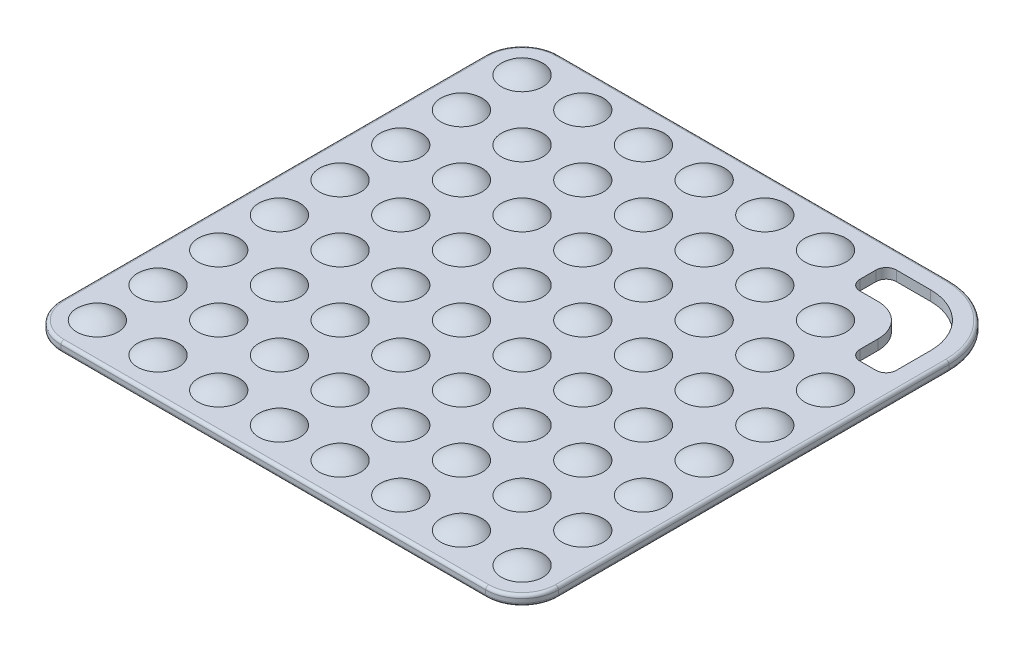
SolidWorks part; units mm, degrees
material "Natural Rubber"
ref_plane "Front Plane" through (0, 0, 0) normal (0, 0, 1) x (1, 0, 0)
ref_plane "Top Plane" through (0, 0, 0) normal (0, 1, 0) x (1, 0, 0)
ref_plane "Right Plane" through (0, 0, 0) normal (1, 0, 0) x (0, 0, -1)
sketch "Sketch1" plane through (0, 0, 0) normal (0, 1, 0) x (1, 0, 0)
  line L1 (-105, 123) -> (88, 123)
  line L2 (-123, 105) -> (-123, -105)
  line L3 (-105, -123) -> (105, -123)
  line L4 (123, 88) -> (123, -105)
  line L5 (-123, 123) -> (123, -123) construction
  line L6 (-123, -123) -> (123, 123) construction
  arc A0 (88, 123) -> (123, 88) centre (88, 88) cw
  arc A1 (105, -123) -> (123, -105) centre (105, -105) ccw
  arc A2 (-105, 123) -> (-123, 105) centre (-105, 105) ccw
  arc A3 (-123, -105) -> (-105, -123) centre (-105, -105) ccw
  point P0 (0, 0)
  dimension "D3" = 35
  dimension "D4" = 18
  dimension "D1" = 246
  dimension "D2" = 246
extrude "Boss-Extrude1" add sketch "Sketch1" along normal blind 5
ref_plane "Plane1" through (0, 0, 105) normal (0, 0, 1) x (1, 0, 0)
sketch "Sketch3" plane through (0, 0, 105) normal (0, 0, 1) x (1, 0, 0)
  line L1 (123, 5) -> (105, 5) construction
  line L2 (105, 5) -> (115.198, 5)
  line L3 (105, 9) -> (105, 5)
  arc A0 (105, 9) -> (115.198, 5) centre (105, -6) cw
  dimension "D1" = 4
  dimension "D2" = 15
revolve "Revolve4" add sketch "Sketch3" angle 360 about L3
pattern_linear "LPattern1" count 8 spacing 30 along (-1, 0, 0) count 8 spacing 30 along (0, 0, -1) skipping (0, 6), (0, 7), (1, 7) of "Revolve4"
sketch "Sketch4" plane through (0, 0, 0) normal (0, 1, 0) x (1, 0, 0)
  line L0 (88, 114) -> (71, 114)
  line L1 (66, 109) -> (66, 101)
  line L2 (71, 96) -> (80, 96)
  line L3 (96, 80) -> (96, 71)
  line L4 (101, 66) -> (109, 66)
  line L5 (114, 71) -> (114, 88)
  arc A0 (123, 88) -> (88, 123) centre (88, 88) ccw construction
  arc A1 (123, 88) -> (88, 123) centre (88, 88) ccw construction
  arc A2 (88, 114) -> (114, 88) centre (88, 88) cw
  arc A4 (80, 96) -> (96, 80) centre (80, 80) cw
  arc A5 (109, 66) -> (114, 71) centre (109, 71) ccw
  arc A6 (96, 71) -> (101, 66) centre (101, 71) ccw
  arc A7 (66, 101) -> (71, 96) centre (71, 101) ccw
  arc A8 (71, 114) -> (66, 109) centre (71, 109) ccw
  point P10 (83.829, 83.829)
  point P13 (0, 0)
  point P14 (85.198, 85.198)
  point P15 (84.3898, 84.3898)
  dimension "D1" = 26
  dimension "D2" = 18
  dimension "D4" = 16
  dimension "D5" = 5
  dimension "D3" = 22
extrude "Cut-Extrude1" cut sketch "Sketch4" against normal through all and the other way through all
fillet "Fillet1" radius 1.5 16 edges at (112.7487, 0, -112.7487) (123, 0, 8.5) (117.7279, 0, 117.7279) (0, 0, 123) (-117.7279, 0, 117.7279) (-123, 0, 0) (-117.7279, 0, -117.7279) (112.7487, 5, -112.7487) (123, 5, 8.5) (117.7279, 5, 117.7279) (0, 5, 123) (-117.7279, 5, 117.7279) (-123, 5, 0) (-117.7279, 5, -117.7279) (-8.5, 0, -123) (-8.5, 5, -123)
